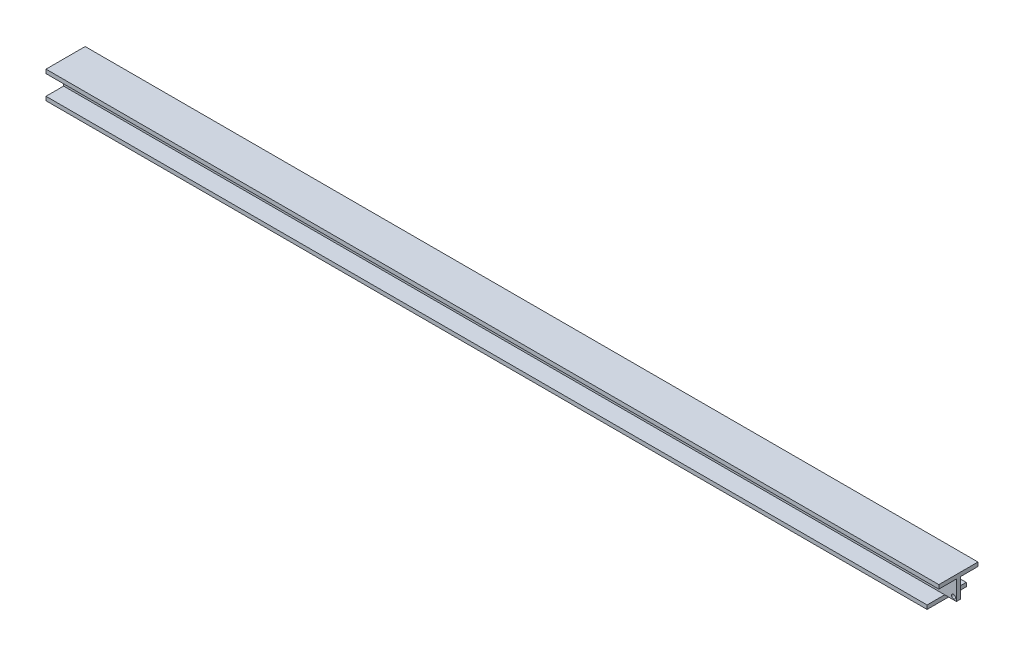
SolidWorks part; units mm, degrees
material "Stainless Steel (ferritic)"
ref_plane "Front" through (0, 0, 0) normal (0, 0, 1) x (1, 0, 0)
ref_plane "Top" through (0, 0, 0) normal (0, 1, 0) x (1, 0, 0)
ref_plane "Right" through (0, 0, 0) normal (1, 0, 0) x (0, 0, -1)
sketch "Sketch1" plane through (0, 0, 0) normal (1, 0, 0) x (0, 0, -1)
  line L0 (139.7, 0) -> (254, 0)
  line L1 (0, 0) -> (114.3, 0)
  line L2 (0, 0) -> (0, 25.4)
  line L3 (0, 25.4) -> (254, 25.4)
  line L4 (254, 0) -> (254, 25.4)
  line L6 (114.3, 0) -> (114.3, -127)
  line L8 (139.7, 0) -> (139.7, -127)
  line L9 (0, -127) -> (114.3, -127)
  line L10 (0, -127) -> (0, -152.4)
  line L11 (0, -152.4) -> (254, -152.4)
  line L12 (254, -127) -> (254, -152.4)
  line L13 (139.7, -127) -> (254, -127)
  dimension "D1" = 127
  dimension "D2" = 254
  dimension "D3" = 25.4
  dimension "D4" = 152.4
extrude "Boss-Extrude1" add sketch "Sketch1" along normal blind 1930.4
sketch "Sketch2" plane through (0, 0, -114.3) normal (0, 0, 1) x (1, 0, 0)
  line L0 (1930.4, 0) -> (1930.4, -127) construction
  line L1 (1930.4, -127) -> (0, -127) construction
  circle A0 centre (1911.35, -107.95) radius 12.7
  dimension "D1" = 25.4
  dimension "D2" = 19.05
  dimension "D3" = 19.05
extrude "Cut-Extrude1" cut sketch "Sketch2" against normal up to next
sketch "Sketch3" plane through (1930.4, 0, 0) normal (1, 0, 0) x (0, 0, -1)
  line L1 (0, -127) -> (254, -127)
  line L2 (0, -127) -> (0, -152.4)
  line L3 (0, -152.4) -> (254, -152.4)
  line L4 (254, -127) -> (254, -152.4)
extrude "Cut-Extrude2" cut sketch "Sketch3" against normal blind 76.2
sketch "Sketch5" plane through (0, 0, 0) normal (-1, 0, 0) x (0, 0, 1)
  line L0 (-254, 25.4) -> (0, 25.4)
  line L1 (0, 25.4) -> (0, 0)
  line L2 (0, 0) -> (-114.3, 0)
  line L3 (-114.3, 0) -> (-114.3, -127)
  line L4 (-114.3, -127) -> (0, -127)
  line L5 (0, -127) -> (0, -152.4)
  line L6 (0, -152.4) -> (-254, -152.4)
  line L7 (-254, -152.4) -> (-254, -127)
  line L8 (-254, -127) -> (-139.7, -127)
  line L9 (-139.7, -127) -> (-139.7, 0)
  line L10 (-139.7, 0) -> (-254, 0)
  line L11 (-254, 0) -> (-254, 25.4)
extrude "Boss-Extrude2" add sketch "Sketch5" along normal blind 3860.8
